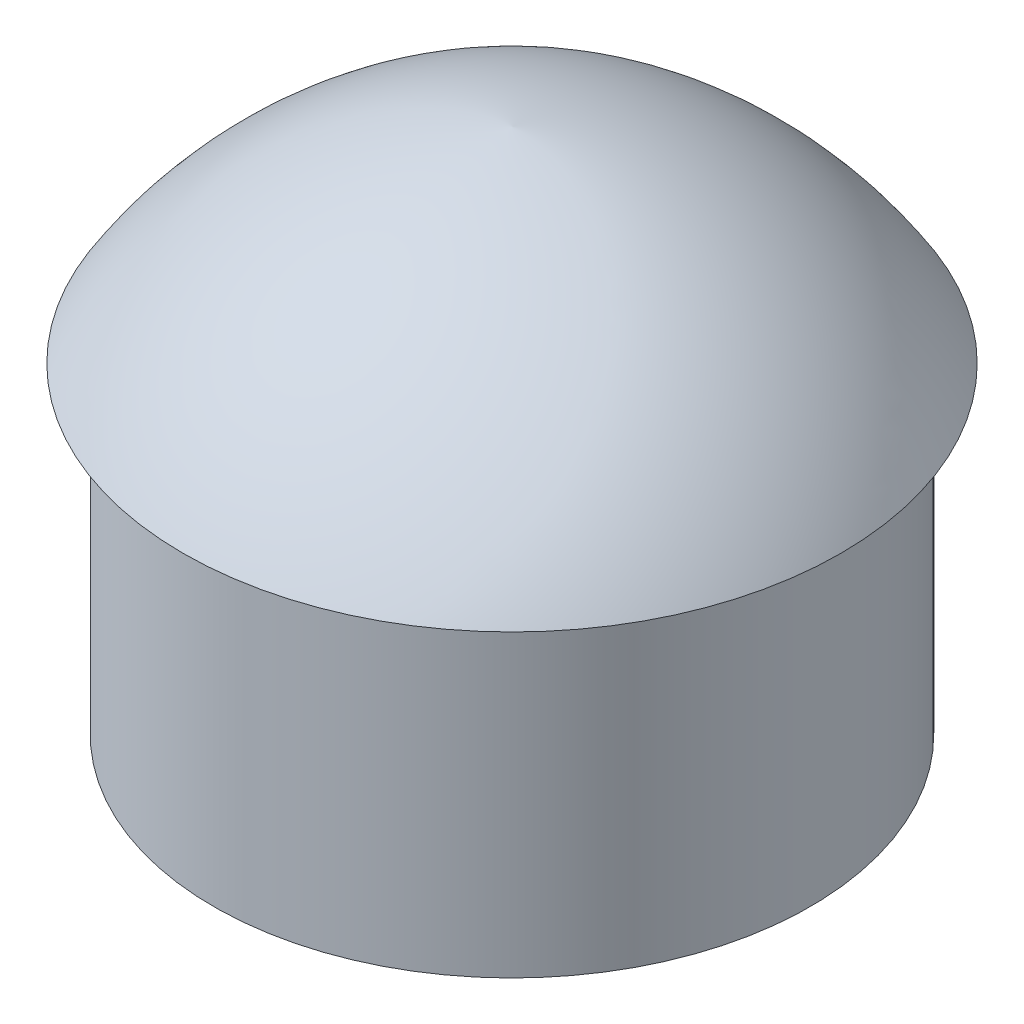
SolidWorks part; units mm, degrees
ref_plane "Front Plane" through (0, 0, 0) normal (0, 0, 1) x (1, 0, 0)
ref_plane "Top Plane" through (0, 0, 0) normal (0, 1, 0) x (1, 0, 0)
ref_plane "Right Plane" through (0, 0, 0) normal (1, 0, 0) x (0, 0, -1)
sketch "Sketch1" plane through (0, 0, 0) normal (0, 0, 1) x (1, 0, 0)
  line L0 (0, 12) -> (0, -12)
  line L1 (0, -12) -> (13.6, -12)
  line L2 (13.6, -12) -> (13.6, 2.6544)
  line L3 (13.6, 2.6544) -> (15, 2.6544)
  arc A0 (15, 2.6544) -> (0, 12) centre (-1.9878, -7.901) ccw
  point P3 (0, 12.6811)
  point P4 (0, 0)
  point P7 (0, 14.3323)
  point P10 (0, 13.6397)
  point P11 (0, 12.8626)
  dimension "D1" = 24
  dimension "D2" = 13.6
  dimension "D3" = 15
revolve "Revolve1" add sketch "Sketch1" angle 360 about L0
